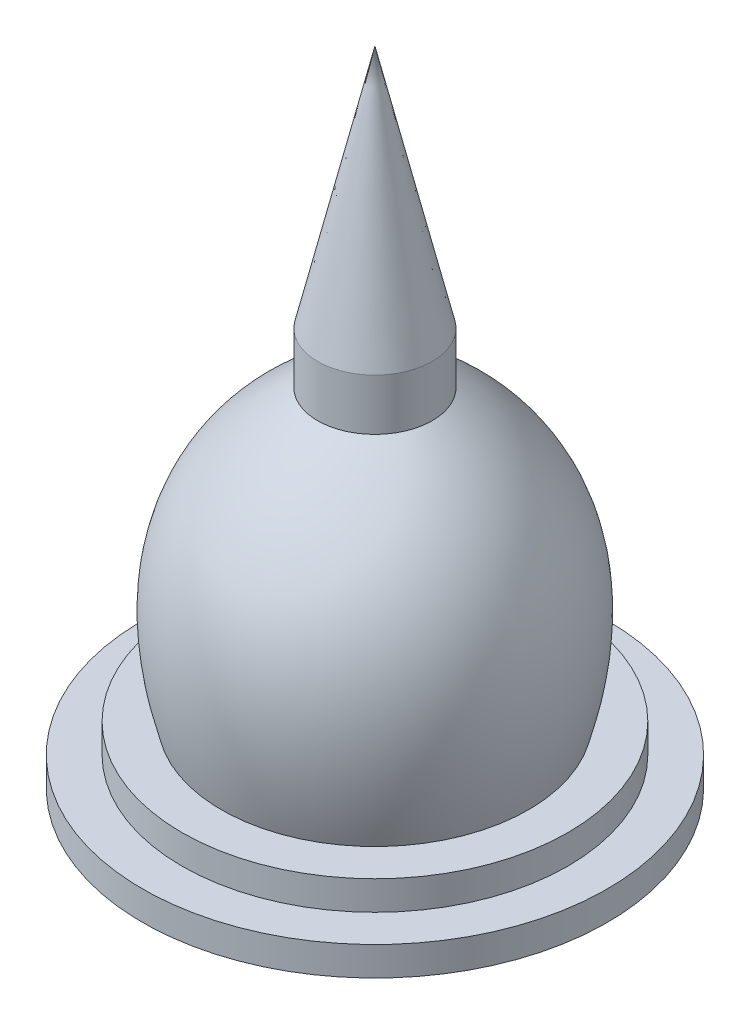
SolidWorks part; units mm, degrees
ref_plane "Front Plane" through (0, 0, 0) normal (0, 0, 1) x (1, 0, 0)
ref_plane "Top Plane" through (0, 0, 0) normal (0, 1, 0) x (1, 0, 0)
ref_plane "Right Plane" through (0, 0, 0) normal (1, 0, 0) x (0, 0, -1)
sketch "Sketch1" plane through (0, 0, 0) normal (0, 0, 1) x (1, 0, 0)
  line L0 (0, 0) -> (0, 120.0387) construction
  line L1 (0, 0) -> (-60, 0)
  line L2 (-60, 0) -> (-60, 7.5011)
  line L3 (-49.8183, 15.0034) -> (-39.6365, 15.0034)
  line L4 (-14.8078, 89.5954) -> (-14.8078, 102.8571)
  line L5 (-14.8078, 102.8571) -> (0, 165.9745)
  line L6 (-49.8183, 15.0034) -> (-49.8183, 7.5023)
  line L7 (-49.8183, 7.5023) -> (-60, 7.5011)
  line L9 (0, 0) -> (0, 165.9745)
  line L10 (0, 165.9745) -> (0, 0)
  line L12 (0, 120.0387) -> (0, 183.2545) construction
  spline S0 degree 2 poles (-39.6365, 15.0034) (-53.8427, 64.8006) (-14.8078, 89.5954) knots 0 0 0 1 1 1
  dimension "D1" = 60
revolve "Revolve1" add sketch "Sketch1" angle 360 about L9
scale "Scale1" scale about centroid uniform scaling yes scale factor 3
scale "Scale2" bodies to scale 102 scale about centroid uniform scaling yes scale factor 1
